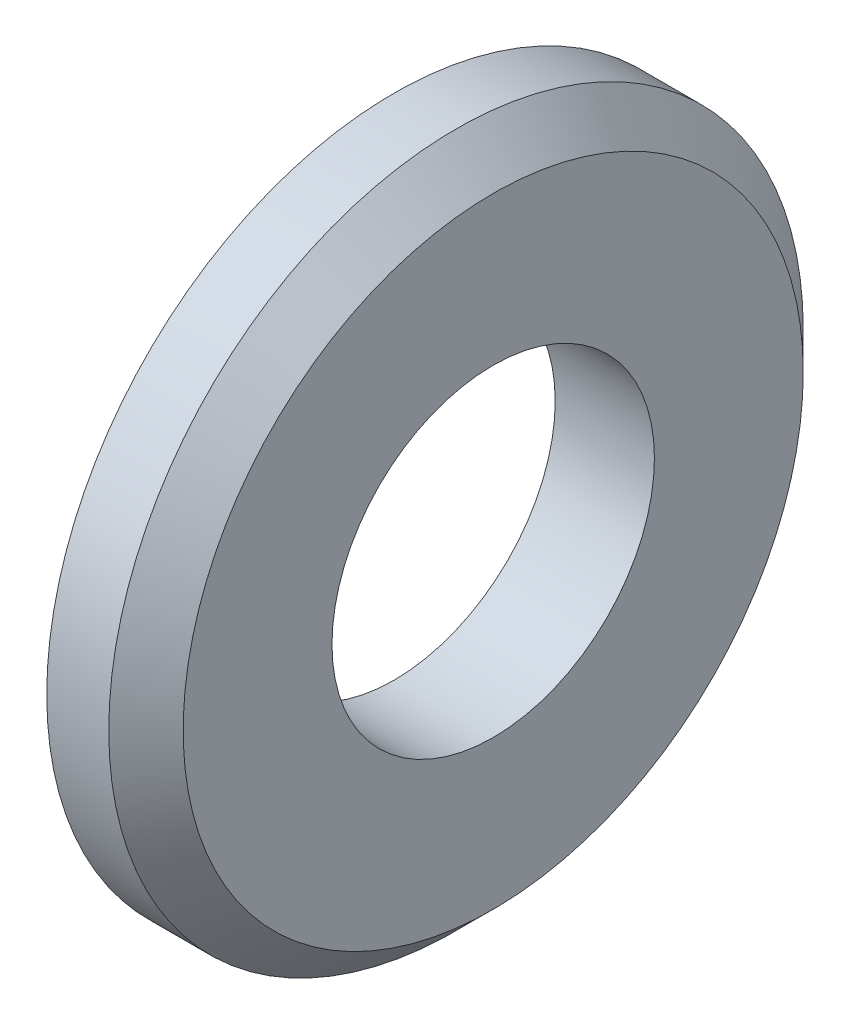
SolidWorks part; units mm, degrees
material "Q235A"
ref_plane "前视基准面" through (0, 0, 0) normal (0, 0, 1) x (1, 0, 0)
ref_plane "上视基准面" through (0, 0, 0) normal (0, 1, 0) x (1, 0, 0)
ref_plane "右视基准面" through (0, 0, 0) normal (1, 0, 0) x (0, 0, -1)
sketch "草图1" plane through (0, 0, 0) normal (0, 0, 1) x (1, 0, 0)
  line L0 (0, 0) -> (-45.2296, 0) construction
  line L1 (0, 6.5) -> (0, 14)
  line L2 (0, 14) -> (-4, 14)
  line L3 (-4, 14) -> (-4, 6.5)
  line L4 (-4, 6.5) -> (0, 6.5)
  line L5 (0, 6.5) -> (0, -6.0177) construction
  line L6 (-4, 6.5) -> (-4, -7.3689) construction
  dimension "D1" = 4
  dimension "D2" = 13
  dimension "D3" = 28
revolve "旋转1" add sketch "草图1" angle 360 about L0
chamfer "倒角2" distance 1.5 angle 45 1 edges at (0, 0, -14)
